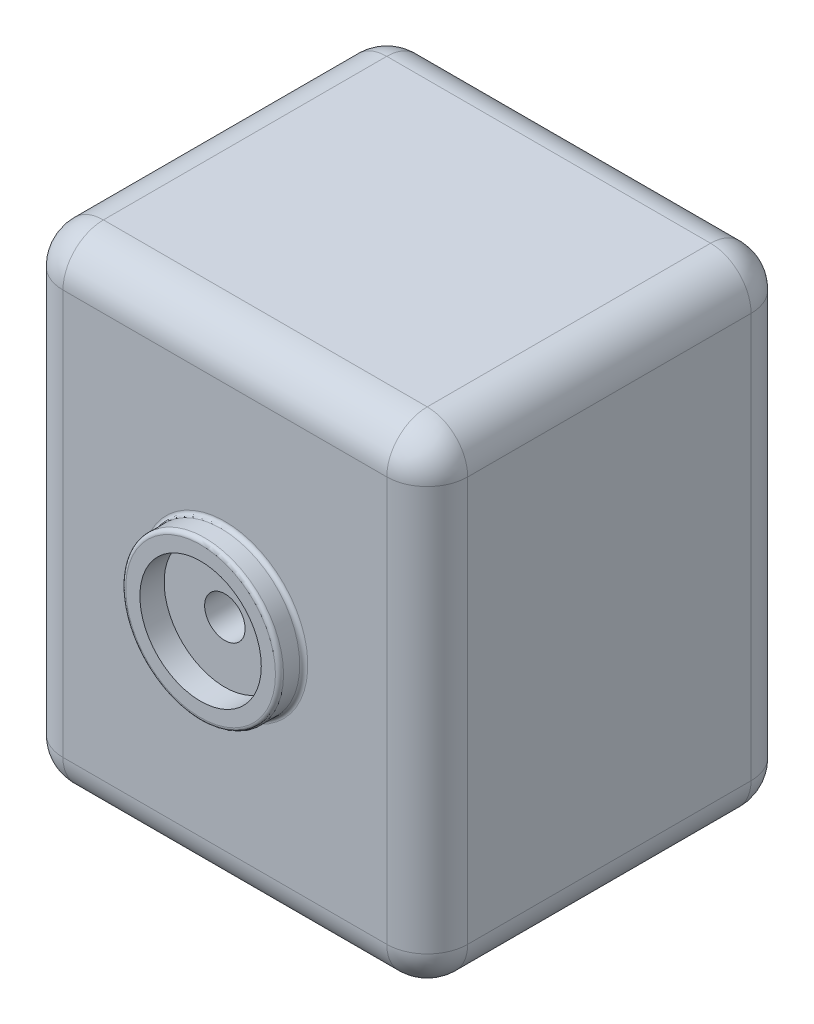
SolidWorks part; units mm, degrees
material "Brass"
ref_plane "Front Plane" through (0, 0, 0) normal (0, 0, 1) x (1, 0, 0)
ref_plane "Top Plane" through (0, 0, 0) normal (0, 1, 0) x (1, 0, 0)
ref_plane "Right Plane" through (0, 0, 0) normal (1, 0, 0) x (0, 0, -1)
sketch "Sketch1" plane through (0, 0, 0) normal (0, 0, 1) x (1, 0, 0)
  line L1 (0, 0) -> (10, 0)
  line L2 (0, 0) -> (0, 12)
  line L3 (0, 12) -> (10, 12)
  line L4 (10, 0) -> (10, 12)
  dimension "D1" = 12
  dimension "D2" = 10
extrude "Boss-Extrude1" add sketch "Sketch1" against normal blind 9
sketch "Sketch3" plane through (0, 0, 0) normal (0, 0, 1) x (1, 0, 0)
  line L0 (0, 12) -> (0, 0) construction
  line L2 (10, 12) -> (0, 12) construction
  circle A0 centre (5, 6) radius 1.95
  dimension "D3" = 3.9
  dimension "D1" = 5
  dimension "D2" = 6
extrude "Boss-Extrude2" add sketch "Sketch3" along normal blind 0.6
sketch "Sketch5" plane through (0, 0, 0.6) normal (0, 0, 1) x (1, 0, 0)
  circle A0 centre (5, 6) radius 1.5
  dimension "D1" = 3
extrude "Cut-Extrude1" cut sketch "Sketch5" against normal blind 0.6
sketch "Sketch7" plane through (0, 0, 0) normal (0, 0, 1) x (1, 0, 0)
  circle A0 centre (5, 6) radius 0.5
  dimension "D1" = 1
extrude "Cut-Extrude2" cut sketch "Sketch7" against normal through all
fillet "Fillet1" radius 1 12 edges at (5, 12, 0) (10, 12, -4.5) (10, 6, 0) (10, 0, -4.5) (5, 0, 0) (0, 0, -4.5) (0, 12, -4.5) (0, 6, 0) (5, 0, -9) (10, 6, -9) (5, 12, -9) (0, 6, -9)
fillet "Fillet2" radius 0.1 2 edges at (6.95, 6, 0.6) (3.05, 6, 0)
